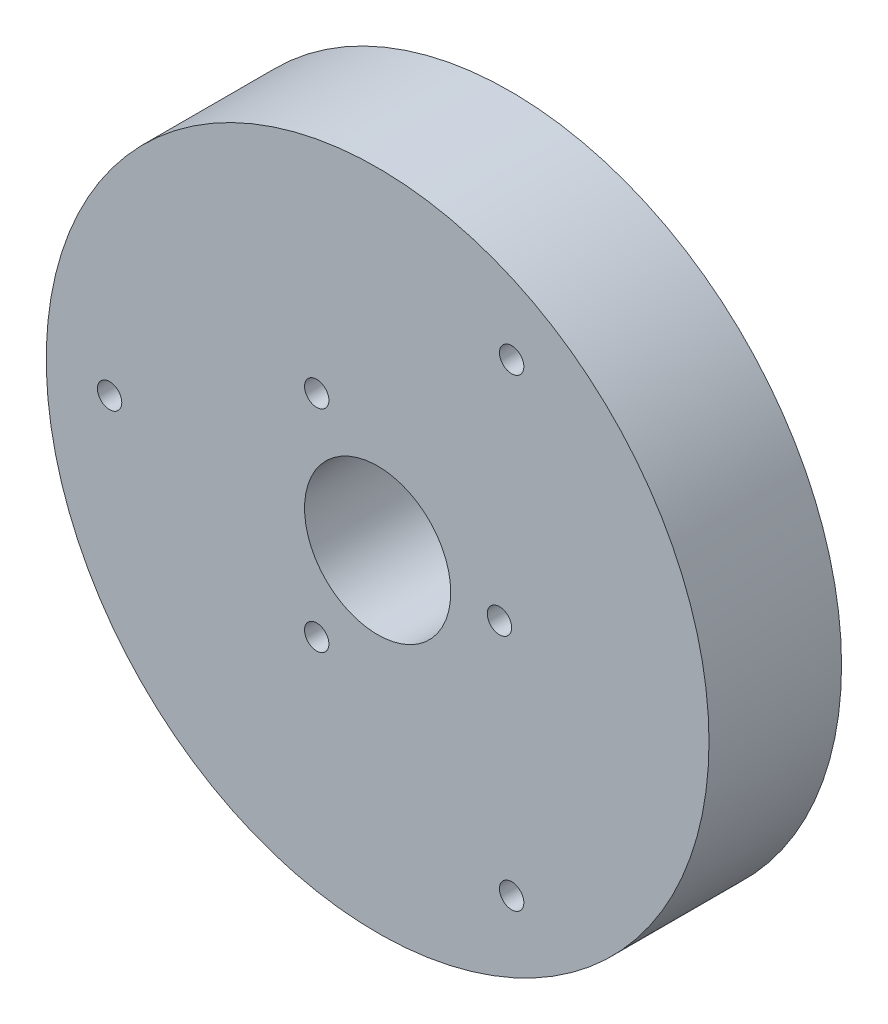
SolidWorks part; units mm, degrees
ref_plane "Спереди" through (0, 0, 0) normal (0, 0, 1) x (1, 0, 0)
ref_plane "Сверху" through (0, 0, 0) normal (0, 1, 0) x (1, 0, 0)
ref_plane "Справа" through (0, 0, 0) normal (1, 0, 0) x (0, 0, -1)
sketch "Эскиз1" plane through (0, 0, 0) normal (0, 0, 1) x (1, 0, 0)
  circle A0 centre (0, 0) radius 34
  dimension "D1" = 68
extrude "Бобышка-Вытянуть1" add sketch "Эскиз1" along normal blind 13.6
sketch "Эскиз2" plane through (0, 0, 13.6) normal (0, 0, 1) x (1, 0, 0)
  circle A0 centre (0, 0) radius 16.5
  dimension "D1" = 33
extrude "Бобышка-Вытянуть2" add sketch "Эскиз2" along normal blind 8.9
fillet "Скругление1" radius 1 1 edges at (16.5, 0, 22.5)
sketch "Эскиз3" plane through (0, 0, 0) normal (0, 0, -1) x (-1, 0, 0)
  circle A0 centre (0, 0) radius 4
  dimension "D1" = 8
extrude "Вырез-Вытянуть1" cut sketch "Эскиз3" against normal through all
sketch "Эскиз4" plane through (0, 0, 22.5) normal (0, 0, 1) x (1, 0, 0)
  circle A0 centre (0, 0) radius 7.5
  dimension "D1" = 15
extrude "Вырез-Вытянуть2" cut sketch "Эскиз4" against normal through all
sketch "Эскиз5" [suppressed] plane through (0, 0, 22.5) normal (0, 0, 1) x (1, 0, 0)
  line L0 (0, 15.5) -> (0, -15.5) construction
  line L1 (15.5, 0) -> (-15.5, 0) construction
  circle A0 centre (0, 0) radius 15.5 construction
  circle A1 centre (0, 0) radius 12.5 construction
  dimension "D1" = 25
hole_wizard "Отверстие обработанное метчиком M3x0.51" [suppressed] positions "Эскиз7" profile "Эскиз6" tap size "M3x0.5" standard "Ansi Metric"
sketch "Эскиз7" [suppressed] plane through (0, 0, 22.5) normal (0, 0, 1) x (1, 0, 0)
  line L0 (0, 15.5) -> (0, -15.5) construction
  line L1 (15.5, 0) -> (-15.5, 0) construction
  circle A0 centre (0, 0) radius 12.5 construction
  point P0 (0, 12.5)
  point P6 (12.5, 0)
  point P10 (0, -12.5)
  point P12 (-12.5, 0)
sketch "Эскиз6" plane through (0, 12.5, 22.5) normal (1, 0, 0) x (0, -1, 0)
  line L0 (0, 0) -> (0, 22.5)
  line L1 (0, 22.5) -> (1.25, 22.5)
  line L2 (1.25, 22.5) -> (1.25, 0)
  line L5 (1.25, 0) -> (0, 0)
  line L11 (0, -6.35) -> (0, 107.95) construction
  dimension "Диаметр проходного сверла" = 2.5
  dimension "Глубина проходного сверла" = 22.5
cosmetic thread "Отверстие резьбы1" [suppressed] parameters "D2"=3
cosmetic thread "Отверстие резьбы2" [suppressed] parameters "D2"=3
cosmetic thread "Отверстие резьбы3" [suppressed] parameters "D2"=3
cosmetic thread "Отверстие резьбы4" [suppressed] parameters "D2"=3
sketch "Эскиз8" plane through (0, 0, 22.5) normal (0, 0, 1) x (1, 0, 0)
  line L0 (-15.5, 0) -> (15.5, 0) construction
  line L1 (-7.75, 13.4234) -> (7.75, -13.4234) construction
  line L2 (7.75, 13.4234) -> (-7.75, -13.4234) construction
  circle A0 centre (0, 0) radius 15.5 construction
  circle A1 centre (0, 0) radius 12.5 construction
  dimension "D3" = 25
  dimension "D1" = 60
  dimension "D2" = 60
hole_wizard "Отверстие обработанное метчиком M3x0.52" positions "Эскиз10" profile "Эскиз9" tap size "M3x0.5" standard "Ansi Metric" end condition through all
sketch "Эскиз10" plane through (5.1769, -11.0548, 0) normal (0, 0, 1) x (1, 0, 0)
  line L0 (-12.9269, 24.4782) -> (2.5731, -2.3686) construction
  line L1 (2.5731, 24.4782) -> (-12.9269, -2.3686) construction
  line L2 (-20.6769, 11.0548) -> (10.3231, 11.0548) construction
  circle A0 centre (-5.1769, 11.0548) radius 12.5 construction
  point P0 (-11.4269, 21.8801)
  point P6 (-11.4269, 0.2295)
  point P10 (7.3231, 11.0548)
sketch "Эскиз9" plane through (-6.25, 10.8253, 0) normal (1, 0, 0) x (0, 1, 0)
  line L0 (0, 0) -> (0, 22.5)
  line L1 (0, 22.5) -> (1.25, 22.5)
  line L2 (1.25, 22.5) -> (1.25, 0)
  line L5 (1.25, 0) -> (0, 0)
  line L11 (0, -6.35) -> (0, 107.95) construction
  dimension "Диаметр проходного сверла" = 2.5
  dimension "Глубина проходного сверла" = 22.5
cosmetic thread "Отверстие резьбы14" parameters "D2"=3
cosmetic thread "Отверстие резьбы15" parameters "D2"=3
cosmetic thread "Отверстие резьбы16" parameters "D2"=3
sketch "Эскиз11" plane through (0, 0, 0) normal (0, 0, 1) x (1, 0, 0)
  line L0 (-34, -21.7973) -> (-34, -34) construction
  line L1 (-34, -34) -> (-22.7373, -34) construction
  circle A0 centre (0, 0) radius 34 construction
sketch "Эскиз12" plane through (0, 0, 0) normal (0, 0, 1) x (1, 0, 0)
  line L0 (0, 0) -> (38.8488, 0) construction
  line L1 (0, 0) -> (21.2342, 36.7787) construction
  line L2 (0, 0) -> (20.2354, -35.0488) construction
  line L3 (0, 0) -> (-42.0367, 0) construction
  circle A0 centre (0, 0) radius 27.5 construction
  dimension "D1" = 55
  dimension "D2" = 60
  dimension "D3" = 60
hole_wizard "Отверстие обработанное метчиком M3x0.53" positions "Эскиз14" profile "Эскиз13" tap size "M3x0.5" standard "Ansi Metric" end condition through all
sketch "Эскиз14" plane through (7.746, 28.1911, 0) normal (0, 0, 1) x (1, 0, 0)
  line L0 (-7.746, -28.1911) -> (13.4882, 8.5877) construction
  line L1 (-7.746, -28.1911) -> (-49.7827, -28.1911) construction
  line L2 (-7.746, -28.1911) -> (12.4894, -63.2399) construction
  circle A0 centre (-7.746, -28.1911) radius 27.5 construction
  point P0 (6.004, -4.3754)
  point P6 (-35.246, -28.1911)
  point P10 (6.004, -52.0068)
sketch "Эскиз13" plane through (13.75, 23.8157, 0) normal (1, 0, 0) x (0, 1, 0)
  line L0 (0, 0) -> (0, 22.5)
  line L1 (0, 22.5) -> (1.25, 22.5)
  line L2 (1.25, 22.5) -> (1.25, 0)
  line L5 (1.25, 0) -> (0, 0)
  line L11 (0, -6.35) -> (0, 107.95) construction
  dimension "Диаметр проходного сверла" = 2.5
  dimension "Глубина проходного сверла" = 22.5
cosmetic thread "Отверстие резьбы11" parameters "D2"=3
cosmetic thread "Отверстие резьбы12" parameters "D2"=3
cosmetic thread "Отверстие резьбы13" parameters "D2"=3
sketch "Эскиз15" plane through (0, 0, 22.5) normal (0, 0, 1) x (1, 0, 0)
  circle A0 centre (0, 0) radius 20.2043
extrude "Вырез-Вытянуть3" cut sketch "Эскиз15" against normal up to surface (8.9 mm away) up to face at (15, 23.8157, 13.6)
